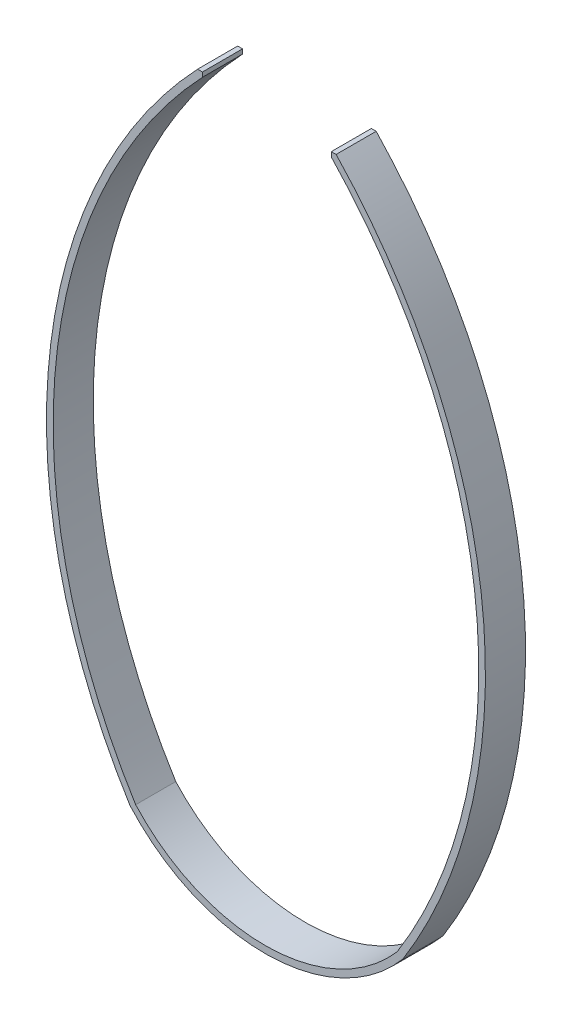
SolidWorks part; units mm, degrees
ref_plane "Plan de face" through (0, 0, 0) normal (0, 0, 1) x (1, 0, 0)
ref_plane "Plan de dessus" through (0, 0, 0) normal (0, 1, 0) x (1, 0, 0)
ref_plane "Plan de droite" through (0, 0, 0) normal (1, 0, 0) x (0, 0, -1)
sketch "Esquisse1" plane through (0, 0, 0) normal (0, 0, 1) x (1, 0, 0)
  line L0 (-50, 263.0077) -> (50, 263.0077) construction
  line L1 (0, 0) -> (0, 109.0003) construction
  line L6 (135.4768, 198.1061) -> (135.4768, -198.1061) construction
  line L7 (-135.4768, 198.1061) -> (-135.4768, -198.1061) construction
  line L12 (46.3684, 259.5708) -> (46.3684, 263.0077)
  line L13 (46.3684, 263.0077) -> (50, 263.0077)
  line L14 (-53.6316, 266.4445) -> (-50, 266.4445)
  line L15 (-50, 266.4445) -> (-50, 263.0077)
  arc A2 (50, 263.0077) -> (99.9773, -233.3633) centre (-246.4467, -17.5416) cw
  arc A3 (99.9773, -233.3633) -> (-104.2211, -236.0071) centre (-3.2655, -146.3567) cw
  arc A4 (-50, 263.0077) -> (-99.9773, -233.3633) centre (246.4467, -17.5416) ccw
  arc A5 (46.3684, 259.5708) -> (95.7335, -230.7194) centre (-246.4467, -17.5416) cw
  arc A6 (-53.6316, 266.4445) -> (-104.2211, -236.0071) centre (246.4467, -17.5416) ccw
  arc A7 (-99.9773, -233.3633) -> (95.7335, -230.7194) centre (-3.2912, -145.4838) ccw
  point P1 (0, 0)
  point P4 (-48.9583, 229.8436)
  point P6 (48.9583, 229.8436)
  point P26 (46.3684, 263.0077)
  point P27 (-50, 266.4445)
  dimension "D1" = 100
  dimension "D4" = 5
extrude "Boss.-Extru.1" add sketch "Esquisse1" along normal blind 30
